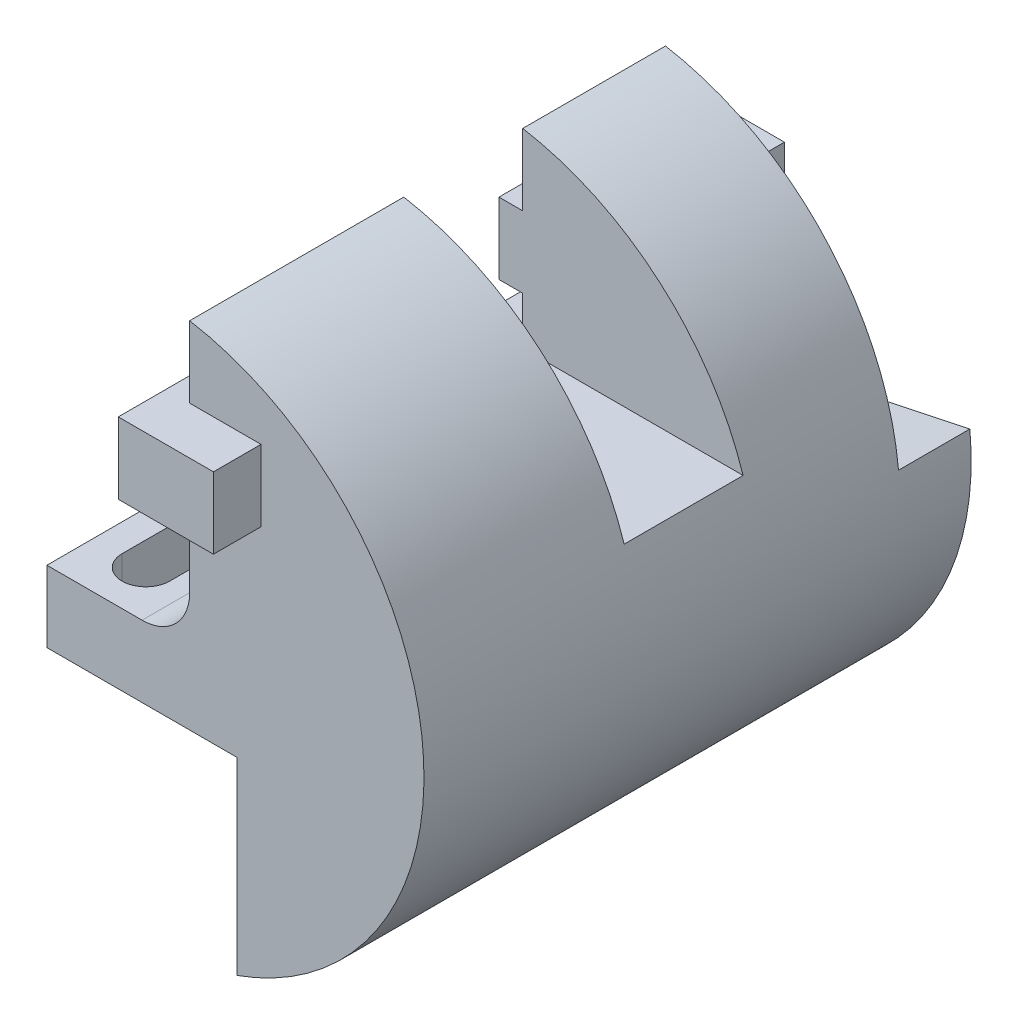
SolidWorks part; units mm, degrees
material "Alliage 1060"
ref_plane "Plan de face" through (0, 0, 0) normal (0, 0, 1) x (1, 0, 0)
ref_plane "Plan de dessus" through (0, 0, 0) normal (0, 1, 0) x (1, 0, 0)
ref_plane "Plan de droite" through (0, 0, 0) normal (1, 0, 0) x (0, 0, -1)
sketch "Esquisse1" plane through (0, 0, 0) normal (0, 0, 1) x (1, 0, 0)
  line L0 (-20, -1.1) -> (0, -1.1)
  line L1 (-20, -1.1) -> (-20, -16.1)
  line L2 (-20, -16.1) -> (20, -16.1)
  line L3 (20, -16.1) -> (20, -55.7724)
  line L4 (10, 8.9) -> (10, 28.4)
  line L5 (10, 28.4) -> (5, 28.4)
  line L6 (5, 28.4) -> (5, 43.4)
  line L7 (5, 43.4) -> (10, 43.4)
  line L8 (10, 43.4) -> (10, 58.4)
  arc A3 (10, 58.4) -> (20, -55.7724) centre (0, 0) cw
  arc A4 (0, -1.1) -> (10, 8.9) centre (0, 8.9) ccw
  dimension "D1" = 59.25
  dimension "D9" = 10
  dimension "D2" = 40
  dimension "D4" = 15
  dimension "D5" = 20
  dimension "D6" = 5
  dimension "D7" = 5
  dimension "D8" = 59.5
  dimension "D3" = 10
  dimension "D10" = 15
  dimension "D11" = 15
extrude "Boss.-Extru.1" add sketch "Esquisse1" along normal blind 100
sketch "Esquisse2" plane through (0, 0, 100) normal (0, 0, 1) x (1, 0, 0)
  line L0 (5, 43.4) -> (25, 43.4)
  line L1 (25, 43.4) -> (25, 28.4)
  line L2 (25, 28.4) -> (5, 28.4)
  line L3 (5, 28.4) -> (5, 43.4)
  dimension "D1" = 20
extrude "Boss.-Extru.2" add sketch "Esquisse2" along normal blind 10
sketch "Esquisse3" plane through (0, 0, 0) normal (0, 0, -1) x (-1, 0, 0)
  line L4 (-5, 43.4) -> (-25, 43.4)
  line L5 (-25, 43.4) -> (-25, 28.4)
  line L6 (-25, 28.4) -> (-5, 28.4)
  line L7 (-5, 28.4) -> (-5, 43.4)
  line L8 (-5, 43.4) -> (-25, 43.4)
  line L9 (-25, 43.4) -> (-25, 28.4)
  line L10 (-25, 28.4) -> (-5, 28.4)
  line L11 (-5, 28.4) -> (-5, 43.4)
  dimension "D1" = 0
extrude "Boss.-Extru.3" add sketch "Esquisse3" along normal blind 10
sketch "Esquisse4" plane through (5, 0, 0) normal (-1, 0, 0) x (0, 0, 1)
  line L0 (30, 77.4352) -> (30, 18.4)
  line L3 (30, 18.4) -> (55, 18.4)
  line L5 (55, 18.4) -> (55, 77.4352)
  line L6 (55, 77.4352) -> (30, 77.4352)
  line L7 (0, 58.4) -> (0, 43.4) construction
  line L8 (100, 28.4) -> (0, 28.4) construction
  dimension "D3" = 10
  dimension "D1" = 25
  dimension "D2" = 30
extrude "Enlèv. mat.-Extru.1" cut sketch "Esquisse4" against normal through all both and the other way through all
sketch "Esquisse5" plane through (0, 0, 0) normal (0, 0, -1) x (-1, 0, 0)
  line L0 (20, -11.1) -> (-58.9764, 5.687)
  line L9 (20, -1.1) -> (0, -1.1)
  line L10 (-10, 8.9) -> (-10, 28.4)
  line L11 (-10, 28.4) -> (-5, 28.4)
  line L12 (-5, 28.4) -> (-5, 43.4)
  line L13 (-5, 43.4) -> (-10, 43.4)
  line L14 (-10, 43.4) -> (-10, 58.4)
  line L15 (-20, -55.7724) -> (-20, -16.1)
  line L16 (-20, -16.1) -> (20, -16.1)
  line L17 (20, -16.1) -> (20, -1.1)
  line L19 (-10, 8.9) -> (-10, 28.4)
  line L20 (-10, 28.4) -> (-5, 28.4)
  line L21 (-5, 28.4) -> (-5, 43.4)
  line L22 (-5, 43.4) -> (-10, 43.4)
  line L23 (-10, 43.4) -> (-10, 58.4)
  line L24 (-20, -55.7724) -> (-20, -16.1)
  line L25 (-20, -16.1) -> (20, -16.1)
  line L26 (20, -16.1) -> (20, -11.1)
  arc A2 (-10, 8.9) -> (0, -1.1) centre (0, 8.9) ccw
  arc A3 (-10, 58.4) -> (-20, -55.7724) centre (0, 0) ccw
  arc A5 (-58.9764, 5.687) -> (-20, -55.7724) centre (0, 0) ccw
  arc M16 (-10, 58.4) -> (-20, -55.7724) centre (0, 0) ccw
  line M17 (-20, -55.7724) -> (-20, -16.1)
  line M18 (-20, -16.1) -> (20, -16.1)
  line M19 (20, -16.1) -> (20, -1.1)
  dimension "D2" = 5
  dimension "D3" = 78
  dimension "D1" = 0
extrude "Boss.-Extru.4" add sketch "Esquisse5" along normal blind 15 contours L0 M19 M16 M17 M18
sketch "Esquisse6" plane through (0, -1.1, 0) normal (0, 1, 0) x (1, 0, 0)
  line L0 (-9.202, -10) -> (-9.202, -90) construction
  line L1 (-4.202, -10) -> (-4.202, -90)
  line L2 (-14.202, -10) -> (-14.202, -90)
  line L3 (0, 0) -> (-20, 0) construction
  arc A0 (-4.202, -10) -> (-14.202, -10) centre (-9.202, -10) ccw
  arc A1 (-14.202, -90) -> (-4.202, -90) centre (-9.202, -90) ccw
  point P2 (-9.202, -50)
  point P7 (0, 0)
  dimension "D3" = 5
  dimension "D1" = 80
  dimension "D2" = 10
extrude "Enlèv. mat.-Extru.2" cut sketch "Esquisse6" against normal through all both and the other way through all
equation "\"A\" = 59.25"
equation "\"B\" = 59.5"
equation "\"C\"= 25"
equation "\"D8@Esquisse1\"=\"B\""
equation "\"D1@Esquisse1\"=\"A\""
equation "\"D1@Esquisse4\"=\"C\""
